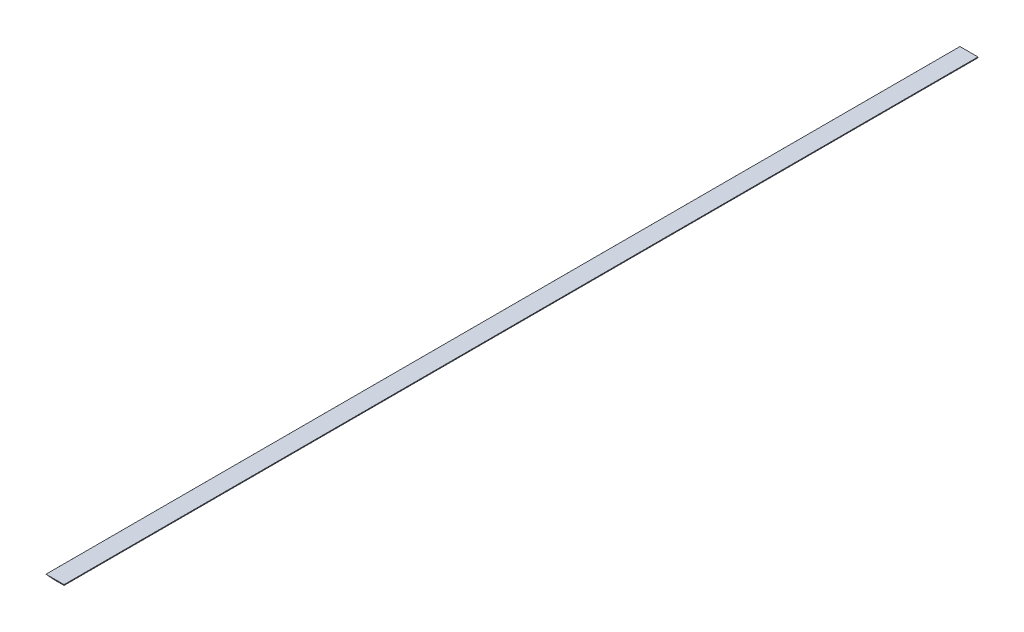
SolidWorks part; units mm, degrees
material "ASTM A500 Grade B Steel"
ref_plane "Front Plane" through (0, 0, 0) normal (0, 0, 1) x (1, 0, 0)
ref_plane "Top Plane" through (0, 0, 0) normal (0, 1, 0) x (1, 0, 0)
ref_plane "Right Plane" through (0, 0, 0) normal (1, 0, 0) x (0, 0, -1)
sketch "Sketch1" plane through (0, 0, 0) normal (0, 0, 1) x (1, 0, 0)
  line L0 (0, 0) -> (53.975, 0)
  line L1 (53.975, 0) -> (53.975, 4.1666)
  line L2 (53.975, 4.1666) -> (-47.625, 4.1666)
  line L3 (-47.625, 4.1666) -> (0, 0)
  dimension "D1" = 175
  dimension "D2" = 101.6
  dimension "D3" = 53.975
extrude "Boss-Extrude1" add sketch "Sketch1" along normal blind 5000
fillet "Fillet1" radius 0.127 1 edges at (-47.625, 4.1666, 2500)
